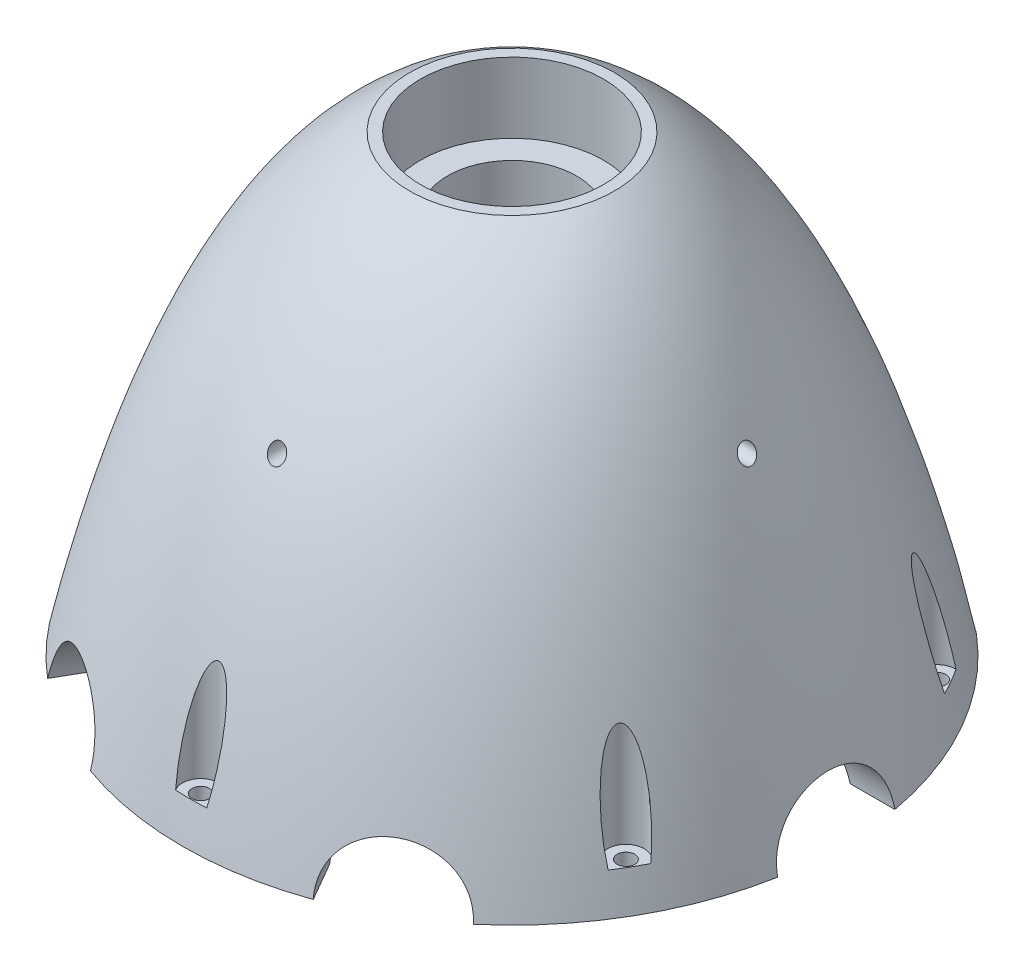
SolidWorks part; units mm, degrees
material "ABS"
ref_plane "前视基准面" through (0, 0, 0) normal (0, 0, 1) x (1, 0, 0)
ref_plane "上视基准面" through (0, 0, 0) normal (0, 1, 0) x (1, 0, 0)
ref_plane "右视基准面" through (0, 0, 0) normal (1, 0, 0) x (0, 0, -1)
sketch "草图2" plane through (0, 0, 0) normal (0, 0, 1) x (1, 0, 0)
  line L0 (0, 0) -> (0, 68.1929) construction
  line L1 (49.53, 0) -> (57.15, 0)
  line L2 (43.7969, 21.463) -> (49.53, 0)
  line L3 (14.9225, 17.653) -> (8.5725, 17.653)
  line L4 (8.5725, 17.653) -> (8.5725, 27.813)
  line L5 (8.5725, 27.813) -> (41.7922, 27.813)
  line L6 (26.4222, 60.198) -> (35.9686, 43.053)
  line L7 (15.875, 76.2) -> (15.875, 66.548)
  line L8 (8.5725, 56.388) -> (8.5725, 66.548)
  line L9 (8.5725, 66.548) -> (15.875, 66.548)
  line L10 (14.9225, 17.653) -> (14.9225, 21.463)
  line L11 (14.9225, 21.463) -> (43.7969, 21.463)
  line L12 (15.875, 76.2) -> (15.875, 78.74)
  line L13 (15.875, 78.74) -> (17.78, 78.74)
  line L14 (13.9743, 56.388) -> (13.9743, 60.198)
  line L15 (13.9743, 60.198) -> (26.4222, 60.198)
  line L16 (13.9743, 56.388) -> (8.5725, 56.388)
  line L17 (35.9686, 43.053) -> (41.7922, 27.813)
  spline S0 degree 2 poles (57.15, 0) (43.1355, 64.1231) (17.78, 78.74) knots 0 0 0 1 1 1
  spline S2 degree 1 poles (49.7057, -1.627) (13.9743, 72.1384) knots 0 0 1 1 construction
  spline S3 degree 3 poles (49.7057, -1.627) (49.4227, -0.3318) (48.8382, 2.2775) (47.654, 7.308) (46.1504, 13.2402) (44.586, 18.8413) (43.4698, 22.5591) (42.8047, 24.6925) (42.1333, 26.7924) (40.6225, 31.3411) (38.8806, 36.0783) (36.7177, 41.3832) (35.1552, 44.9145) (32.4155, 50.5819) (29.8067, 55.2148) (27.2113, 59.1101) (25.5858, 61.3609) (23.7193, 63.7261) (21.4271, 66.2735) (18.9427, 68.6252) (16.874, 70.2634) (15.2136, 71.3954) (14.3947, 71.896) (13.9743, 72.1384) knots 0 0 0 0 0.03125 0.0625 0.125 0.184298 0.215428 0.230993 0.246558 0.277689 0.369173 0.400423 0.462923 0.5 0.625 0.670031 0.701281 0.75 0.8125 0.875 0.9375 0.96875 1 1 1 1 construction
  dimension "D1" = 114.3
  dimension "D2" = 6.35
  dimension "D3" = 10.16
  dimension "D4" = 17.145
  dimension "D5" = 78.74
  dimension "D6" = 2.54
  dimension "D7" = 6.35
  dimension "D8" = 17.78
  dimension "D9" = 5.4018
  dimension "D10" = 7.62
  dimension "D11" = 10.16
  dimension "D12" = 6.35
  dimension "D13" = 7.62
  dimension "D14" = 31.75
  dimension "D15" = 12.192
  dimension "D16" = 32.385
  dimension "D17" = 17.145
revolve "旋转3" add sketch "草图2" angle 360 about L0
ref_plane "基准面1" through (0, 33.02, 0) normal (0, -1, 0) x (1, 0, 0)
sketch "草图3" plane through (0, 33.02, 0) normal (0, -1, 0) x (1, 0, 0)
  circle A0 centre (0, 53.975) radius 1.524
  circle A1 centre (46.7437, 26.9875) radius 1.524
  circle A2 centre (46.7437, -26.9875) radius 1.524
  circle A3 centre (0, -53.975) radius 1.524
  circle A4 centre (-46.7437, -26.9875) radius 1.524
  circle A5 centre (-46.7437, 26.9875) radius 1.524
  point P16 (0, 0)
  dimension "D1" = 3.048
  dimension "D2" = 53.975
  dimension "D3" = 6
extrude "切除-拉伸2" cut sketch "草图3" along normal through all
sketch "草图4" plane through (0, 33.02, 0) normal (0, -1, 0) x (1, 0, 0)
  circle A0 centre (0, 53.975) radius 3.175
  circle A1 centre (46.7437, 26.9875) radius 3.175
  circle A2 centre (46.7437, -26.9875) radius 3.175
  circle A3 centre (0, -53.975) radius 3.175
  circle A4 centre (-46.7437, -26.9875) radius 3.175
  circle A5 centre (-46.7437, 26.9875) radius 3.175
  point P16 (-17.0813, 0)
  dimension "D1" = 6.35
  dimension "D3" = 53.975
extrude "切除-拉伸3" cut sketch "草图4" along normal blind 26.67
sketch "草图5" plane through (0, 0, 0) normal (1, 0, 0) x (0, 0, -1)
  circle A0 centre (0, 0) radius 10.16
  dimension "D1" = 20.32
extrude "切除-拉伸4" cut sketch "草图5" against normal through all
pattern_circular "阵列(圆周)1" count 6 over 360 of "切除-拉伸4"
sketch "Sketch1" plane through (0, 17.653, 0) normal (0, -1, 0) x (1, 0, 0)
  line L0 (-14.5802, 35.1998) -> (-7.1017, 17.145)
  line L1 (14.5802, 35.1998) -> (7.1017, 17.145)
  line L2 (0, 0) -> (0, 40.2261) construction
  line L3 (0, 0) -> (7.1017, 17.145) construction
  line L4 (-7.1017, 17.145) -> (0, 0) construction
  line L5 (-7.1017, 17.145) -> (7.1017, 17.145)
  arc A1 (14.5802, 35.1998) -> (-14.5802, 35.1998) centre (0, 0) ccw
  dimension "D1" = 17.145
  dimension "D2" = 76.2
  dimension "D3" = 22.5
  dimension "D4" = 22.5
extrude "Cut-Extrude1" cut sketch "Sketch1" against normal up to next
fillet "Fillet1" radius 3.175 4 edges at (-7.1017, 24.638, 17.145) (7.1017, 24.638, 17.145) (14.5802, 24.638, 35.1998) (-14.5802, 24.638, 35.1998)
pattern_circular "CirPattern1" count 4 over 360 about axis through (0, 0, 0) along (0, 1, 0) of "Cut-Extrude1", "Fillet1"
sketch "Sketch2" plane through (0, 17.653, 0) normal (0, -1, 0) x (1, 0, 0)
  circle A0 centre (0, 0) radius 11.176
  dimension "D1" = 22.352
extrude "Cut-Extrude2" cut sketch "Sketch2" against normal blind 7.1437
sketch "Sketch3" plane through (0, 66.548, 0) normal (0, 1, 0) x (1, 0, 0)
  circle A0 centre (0, 0) radius 11.176
  dimension "D1" = 22.352
extrude "Cut-Extrude3" cut sketch "Sketch3" against normal blind 7.1437
hole_wizard "Ø3.0mm Dowel Hole1" positions "Sketch4" profile "Sketch5" hole size "Ø3.0" standard "ANSI Metric"
sketch "Sketch4" plane through (0, 0, 0) normal (0, 0, 1) x (1, 0, 0)
  point P0 (0, 50.8)
  dimension "D1" = 50.8
sketch "Sketch5" plane through (0, 50.8, 0) normal (1, 0, 0) x (0, 1, 0)
  line L0 (0, 0) -> (0, 57.15)
  line L1 (0, 57.15) -> (1.5, 57.15)
  line L2 (1.5, 57.15) -> (1.5, 0)
  line L5 (1.5, 0) -> (0, 0)
  line L11 (0, -6.35) -> (0, 107.95) construction
  dimension "Thru Hole Dia." = 3
  dimension "Thru Hole Depth" = 57.15
pattern_circular "CirPattern2" count 4 over 360 about axis through (0, 78.74, 0) along (0, -1, 0) of "Ø3.0mm Dowel Hole1"
